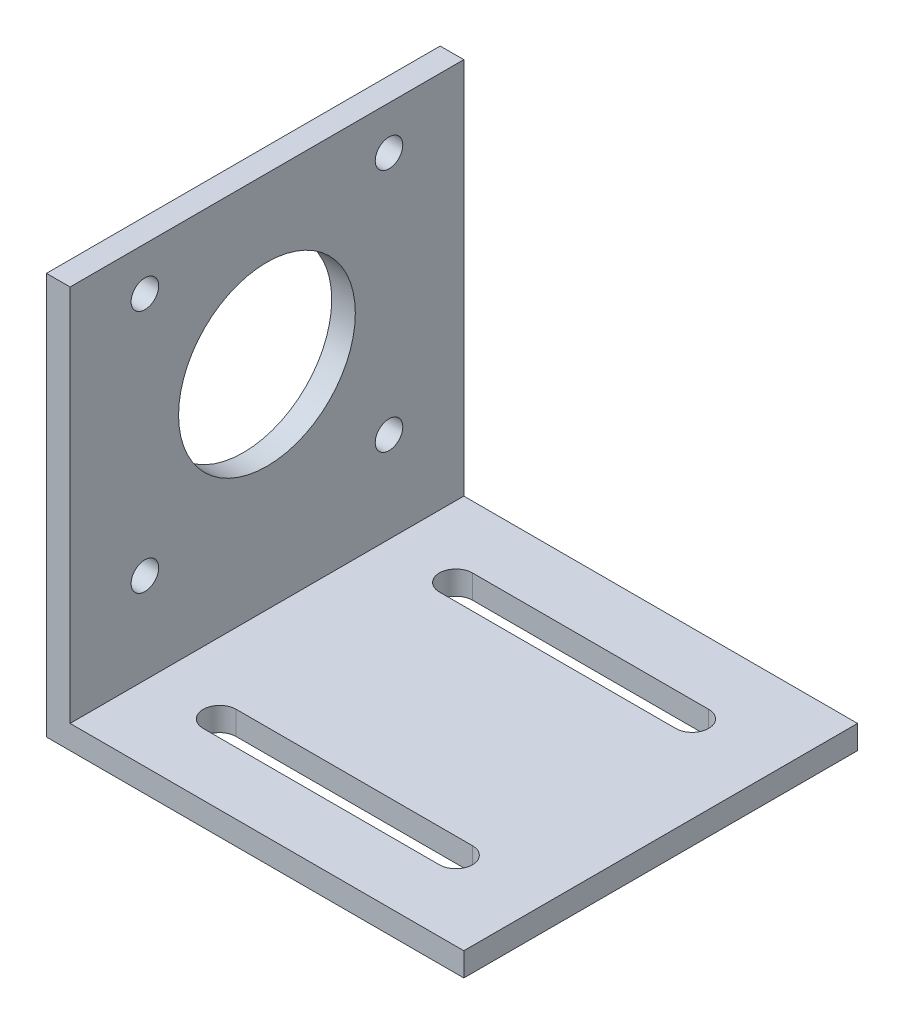
SolidWorks part; units mm, degrees
ref_plane "前视基准面" through (0, 0, 0) normal (0, 0, 1) x (1, 0, 0)
ref_plane "上视基准面" through (0, 0, 0) normal (0, 1, 0) x (1, 0, 0)
ref_plane "右视基准面" through (0, 0, 0) normal (1, 0, 0) x (0, 0, -1)
sketch "草图2" plane through (0, 0, 0) normal (0, 0, 1) x (1, 0, 0)
  line L0 (-23.5, 25.5) -> (-23.5, -22.5)
  line L1 (-26.5, 25.5) -> (-23.5, 25.5)
  line L2 (-26.5, 25.5) -> (-26.5, -25.5)
  line L3 (-26.5, -25.5) -> (26.5, -25.5)
  line L4 (26.5, -22.5) -> (26.5, -25.5)
  line L8 (-23.5, -22.5) -> (26.5, -22.5)
  point P0 (0, 0)
  dimension "D1" = 51
  dimension "D2" = 53
  dimension "D3" = 3
  dimension "D4" = 3
extrude "凸台-拉伸1" add sketch "草图2" along normal blind 50
sketch "草图3" plane through (-23.5, 0, 0) normal (1, 0, 0) x (0, 0, -1)
  line L0 (-50, 25.5) -> (0, 25.5) construction
  circle A0 centre (-25, 4.5) radius 11.2233
  circle A1 centre (-40.5, 20) radius 1.75
  circle A2 centre (-9.5, 20) radius 1.75
  circle A3 centre (-9.5, -11) radius 1.75
  circle A4 centre (-40.5, -11) radius 1.75
  dimension "D4" = 3.5
  dimension "D5" = 3.5
  dimension "D6" = 3.5
  dimension "D7" = 3.5
  dimension "D1" = 21
  dimension "D2" = 31
  dimension "D3" = 31
extrude "切除-拉伸1" cut sketch "草图3" against normal through all
sketch "草图4" plane through (0, -22.5, 0) normal (0, 1, 0) x (1, 0, 0)
  line L1 (-14.5, -7.9) -> (15.5, -7.9)
  line L2 (15.5, -12.1) -> (-14.5, -12.1)
  line L3 (15.5, -37.9) -> (-14.5, -37.9)
  line L4 (-14.5, -42.1) -> (15.5, -42.1)
  arc A0 (15.5, -12.1) -> (15.5, -7.9) centre (15.5, -10) ccw
  arc A1 (15.5, -42.1) -> (15.5, -37.9) centre (15.5, -40) ccw
  arc A2 (-14.5, -37.9) -> (-14.5, -42.1) centre (-14.5, -40) ccw
  arc A3 (-14.5, -7.9) -> (-14.5, -12.1) centre (-14.5, -10) ccw
  point P0 (0.5, -25)
  dimension "D1" = 30
  dimension "D3" = 30
extrude "切除-拉伸2" cut sketch "草图4" against normal through all
sketch "草图6" plane through (-26.5, 0, 0) normal (-1, 0, 0) x (0, 0, 1)
  line L0 (25, 25.5) -> (25, -25.5)
  line L1 (50, 25.5) -> (0, 25.5) construction
  line L2 (50, -25.5) -> (0, -25.5) construction
